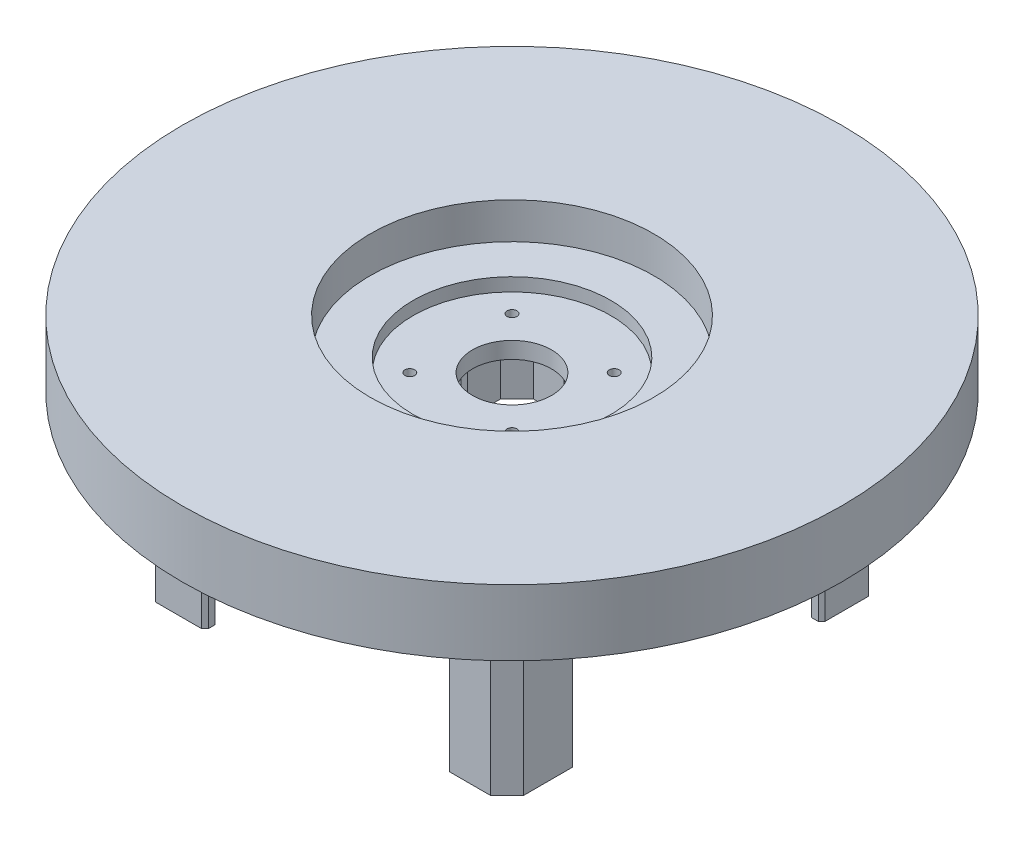
SolidWorks part; units mm, degrees
ref_plane "前视基准面" through (0, 0, 0) normal (0, 0, 1) x (1, 0, 0)
ref_plane "上视基准面" through (0, 0, 0) normal (0, 1, 0) x (1, 0, 0)
ref_plane "右视基准面" through (0, 0, 0) normal (1, 0, 0) x (0, 0, -1)
other "Configuration Table"
sketch "草图1" plane through (0, 0, 0) normal (0, 1, 0) x (1, 0, 0)
  line L0 (0, 0) -> (83.2464, 0) construction
  line L2 (-36.85, 10) -> (-36.85, -10) construction
  line L4 (17.15, 10) -> (17.15, -10) construction
  line L5 (-8.123, 10.2) -> (-8.123, -9.8) construction
  line L7 (-28.623, 10.5) -> (-28.623, -10.5)
  line L8 (-28.623, 10.5) -> (12.377, 10.5)
  line L9 (-28.623, -10.5) -> (12.377, -10.5)
  line L10 (12.377, 10.5) -> (12.377, -10.5)
  circle A0 centre (0, 0) radius 100
  dimension "D1" = 54
  dimension "D4" = 41
  dimension "D8" = 200
  dimension "D2" = 20
  dimension "D3" = 17.15
  dimension "D5" = 10.5
extrude "凸台-拉伸1" add sketch "草图1" along normal blind 5 contours A0
sketch "草图3" plane through (0, 0, 0) normal (0, -1, 0) x (1, 0, 0)
  line L0 (0, 0) -> (0, 109.0175) construction
  circle A0 centre (0, 0) radius 90 construction
  circle A1 centre (0, 90) radius 3
  circle A2 centre (90, 0) radius 3
  circle A3 centre (0, -90) radius 3
  circle A4 centre (-90, 0) radius 3
  dimension "D1" = 4
extrude "切除-拉伸1" cut sketch "草图3" against normal through all
sketch "草图5" plane through (0, 5, 0) normal (0, 1, 0) x (1, 0, 0)
  line L1 (-15.5, -15.5) -> (15.5, -15.5) construction
  line L2 (-15.5, -15.5) -> (-15.5, 15.5) construction
  line L3 (-15.5, 15.5) -> (15.5, 15.5) construction
  line L4 (15.5, -15.5) -> (15.5, 15.5) construction
  line L5 (-15.5, -15.5) -> (15.5, 15.5) construction
  line L6 (-15.5, 15.5) -> (15.5, -15.5) construction
  circle A0 centre (-15.5, 15.5) radius 1.5
  circle A1 centre (15.5, 15.5) radius 1.5
  circle A2 centre (-15.5, -15.5) radius 1.5
  circle A3 centre (15.5, -15.5) radius 1.5
  point P0 (0, 0)
  dimension "D1" = 31
extrude "切除-拉伸2" cut sketch "草图5" against normal through all
sketch "草图6" plane through (0, 5, 0) normal (0, 1, 0) x (1, 0, 0)
  circle A0 centre (0, 0) radius 12
extrude "切除-拉伸3" cut sketch "草图6" against normal through all
sketch "草图7" plane through (0, 5, 0) normal (0, 1, 0) x (1, 0, 0)
  line L0 (0, 0) -> (-90, 0) construction
  line L1 (0, 0) -> (0, 107.0359) construction
  line L2 (-50.8091, 57.3179) -> (-37.5685, 57.3179)
  line L3 (-55.8091, 52.3179) -> (-55.8091, 38.3485)
  line L4 (-55.8091, -52.3179) -> (-55.8091, -36.7886)
  line L5 (-50.8091, -57.3179) -> (-36.8091, -57.3179)
  line L6 (55.8091, -52.3179) -> (55.8091, -37.3905)
  line L7 (50.8091, -57.3179) -> (38.328, -57.3179)
  line L8 (50.8091, 57.3179) -> (37.5685, 57.3179)
  line L9 (55.8091, 52.3179) -> (55.8091, 39.0979)
  line L10 (-51.8091, 48.3179) -> (-51.8091, 38.3485)
  line L11 (-46.8091, 53.3179) -> (-37.5685, 53.3179)
  line L12 (-46.8091, -53.3179) -> (-36.8091, -53.3179)
  line L13 (-51.8091, -48.3179) -> (-51.8091, -36.7886)
  line L14 (51.8091, 48.3179) -> (51.8091, 39.0979)
  line L15 (46.8091, 53.3179) -> (37.5685, 53.3179)
  line L16 (46.8091, -53.3179) -> (38.328, -53.3179)
  line L17 (51.8091, -48.3179) -> (51.8091, -37.3905)
  line L18 (-36.5685, 56.3179) -> (-36.5685, 54.3179)
  line L19 (-54.8091, 37.3485) -> (-52.8091, 37.3485)
  line L20 (52.8091, 38.0979) -> (54.8091, 38.0979)
  line L21 (36.5685, 56.3179) -> (36.5685, 54.3179)
  line L22 (-54.8091, -35.7886) -> (-52.8091, -35.7886)
  line L23 (-35.8091, -54.3179) -> (-35.8091, -56.3179)
  line L24 (37.328, -56.3179) -> (37.328, -54.3179)
  line L25 (52.8091, -36.3905) -> (54.8091, -36.3905)
  line L26 (-55.8091, 57.3179) -> (-36.5685, 57.3179) construction
  line L27 (-55.8091, 57.3179) -> (-55.8091, 37.3485) construction
  line L28 (-55.8091, 52.3179) -> (-50.8091, 57.3179)
  line L29 (-51.8091, 53.3179) -> (-51.8091, 37.3485) construction
  line L30 (-51.8091, 53.3179) -> (-36.5685, 53.3179) construction
  line L31 (-46.8091, 53.3179) -> (-51.8091, 48.3179)
  line L32 (55.8091, 57.3179) -> (36.5685, 57.3179) construction
  line L33 (55.8091, 57.3179) -> (55.8091, 38.0979) construction
  line L34 (55.8091, 52.3179) -> (50.8091, 57.3179)
  line L35 (51.8091, 53.3179) -> (51.8091, 38.0979) construction
  line L36 (51.8091, 53.3179) -> (36.5685, 53.3179) construction
  line L37 (46.8091, 53.3179) -> (51.8091, 48.3179)
  line L38 (-51.8091, -53.3179) -> (-35.8091, -53.3179) construction
  line L39 (-51.8091, -53.3179) -> (-51.8091, -35.7886) construction
  line L40 (-51.8091, -48.3179) -> (-46.8091, -53.3179)
  line L41 (-55.8091, -57.3179) -> (-55.8091, -35.7886) construction
  line L42 (-55.8091, -57.3179) -> (-35.8091, -57.3179) construction
  line L43 (-50.8091, -57.3179) -> (-55.8091, -52.3179)
  line L44 (55.8091, -57.3179) -> (55.8091, -36.3905) construction
  line L45 (55.8091, -57.3179) -> (37.328, -57.3179) construction
  line L46 (50.8091, -57.3179) -> (55.8091, -52.3179)
  line L47 (51.8091, -53.3179) -> (37.328, -53.3179) construction
  line L48 (51.8091, -53.3179) -> (51.8091, -36.3905) construction
  line L49 (51.8091, -48.3179) -> (46.8091, -53.3179)
  line L50 (-37.5685, 53.3179) -> (-36.5685, 54.3179)
  line L51 (-37.5685, 57.3179) -> (-36.5685, 56.3179)
  line L52 (-55.8091, 38.3485) -> (-54.8091, 37.3485)
  line L53 (-51.8091, 38.3485) -> (-52.8091, 37.3485)
  line L54 (55.8091, -37.3905) -> (54.8091, -36.3905)
  line L55 (51.8091, -37.3905) -> (52.8091, -36.3905)
  line L56 (38.328, -53.3179) -> (37.328, -54.3179)
  line L57 (38.328, -57.3179) -> (37.328, -56.3179)
  line L58 (-36.8091, -57.3179) -> (-35.8091, -56.3179)
  line L59 (-36.8091, -53.3179) -> (-35.8091, -54.3179)
  line L60 (-51.8091, -36.7886) -> (-52.8091, -35.7886)
  line L61 (-55.8091, -36.7886) -> (-54.8091, -35.7886)
  line L62 (37.5685, 57.3179) -> (36.5685, 56.3179)
  line L63 (37.5685, 53.3179) -> (36.5685, 54.3179)
  line L64 (51.8091, 39.0979) -> (52.8091, 38.0979)
  line L65 (55.8091, 39.0979) -> (54.8091, 38.0979)
  circle A0 centre (0, 0) radius 80 construction
  dimension "D1" = 4
  dimension "D2" = 4
extrude "凸台-拉伸2" add sketch "草图7" against normal blind 57
sketch "草图9" plane through (0, 5, 0) normal (0, 1, 0) x (1, 0, 0)
  circle A0 centre (0, 0) radius 30
  circle A1 centre (0, 0) radius 100
  circle A2 centre (0, 0) radius 100
  dimension "D1" = 0
extrude "凸台-拉伸4" add sketch "草图9" along normal blind 15
sketch "草图10" plane through (0, 20, 0) normal (0, 1, 0) x (1, 0, 0)
  circle A0 centre (0, 0) radius 43
extrude "切除-拉伸4" cut sketch "草图10" against normal blind 11
